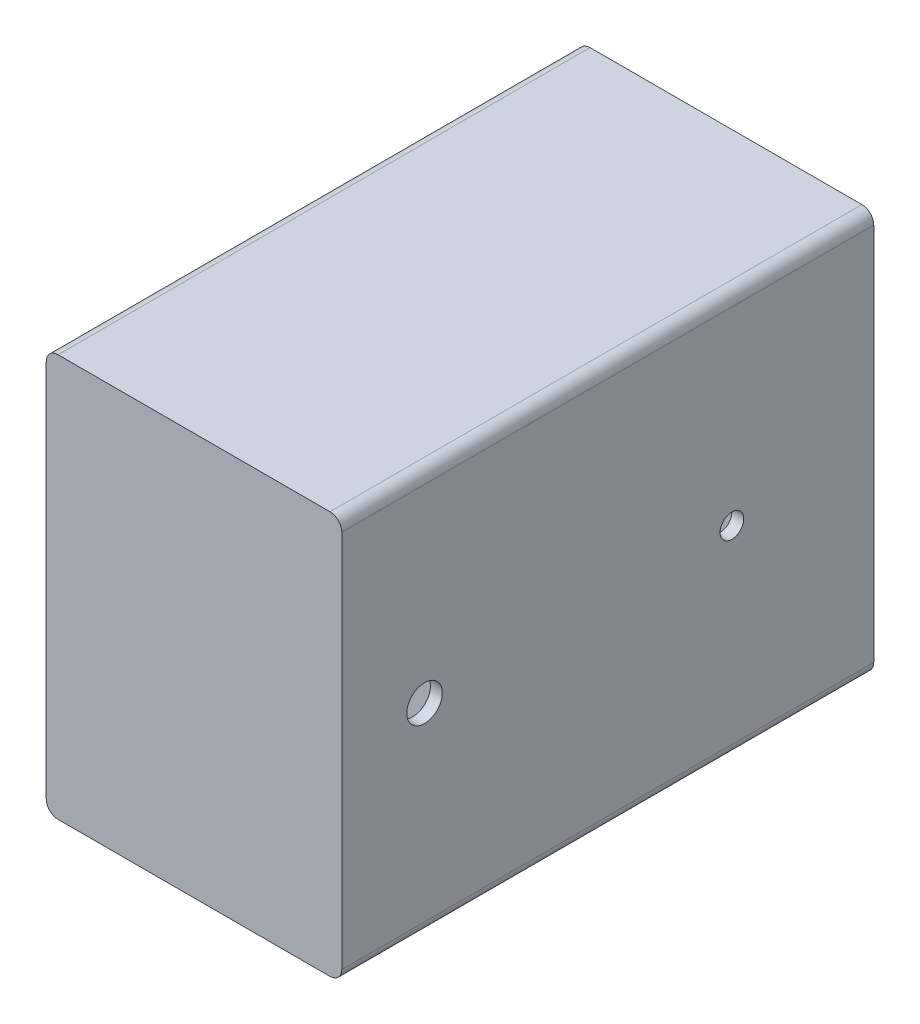
SolidWorks part; units mm, degrees
material "PE 低/中密度"
ref_plane "前视基准面" through (0, 0, 0) normal (0, 0, 1) x (1, 0, 0)
ref_plane "上视基准面" through (0, 0, 0) normal (0, 1, 0) x (1, 0, 0)
ref_plane "右视基准面" through (0, 0, 0) normal (1, 0, 0) x (0, 0, -1)
sketch "草图1" plane through (0, 0, 0) normal (0, 0, 1) x (1, 0, 0)
  line L1 (-125, 170.2) -> (125, 170.2)
  line L2 (-125, 170.2) -> (-125, -170.2)
  line L3 (-125, -170.2) -> (125, -170.2)
  line L4 (125, 170.2) -> (125, -170.2)
  line L5 (-125, 170.2) -> (125, -170.2) construction
  line L6 (-125, -170.2) -> (125, 170.2) construction
  point P0 (0, 0)
  dimension "D1" = 340.4
  dimension "D2" = 250
extrude "凸台-拉伸1" add sketch "草图1" along normal blind 450
fillet "圆角1" radius 10 4 edges at (-125, -170.2, 225) (125, -170.2, 225) (-125, 170.2, 225) (125, 170.2, 225)
sketch "草图4" plane through (125, 0, 0) normal (1, 0, 0) x (0, 0, -1)
  line L1 (-225, 160.2) -> (-225, -90.0252) construction
  line L2 (0, 160.2) -> (-450, 160.2) construction
  line L3 (-120, 0) -> (0, 0) construction
  circle A1 centre (-120, 0) radius 10
  dimension "D1" = 120
extrude "切除-拉伸1" cut sketch "草图4" against normal blind 50
sketch "草图5" plane through (0, 0, 0) normal (0, 0, -1) x (-1, 0, 0)
  line L3 (-30.5, -35.5) -> (30.5, -35.5)
  line L4 (-40.5, -25.5) -> (-40.5, 25.5)
  line L5 (-30.5, 35.5) -> (30.5, 35.5)
  line L6 (40.5, -25.5) -> (40.5, 25.5)
  line L7 (-40.5, -35.5) -> (40.5, 35.5) construction
  line L8 (-40.5, 35.5) -> (40.5, -35.5) construction
  arc A0 (-40.5, 25.5) -> (-30.5, 35.5) centre (-30.5, 25.5) cw
  arc A1 (30.5, -35.5) -> (40.5, -25.5) centre (30.5, -25.5) ccw
  arc A2 (-30.5, -35.5) -> (-40.5, -25.5) centre (-30.5, -25.5) cw
  arc A3 (30.5, 35.5) -> (40.5, 25.5) centre (30.5, 25.5) cw
  point P0 (0, 0)
  dimension "D3" = 10
  dimension "D4" = 10
  dimension "D5" = 10
  dimension "D1" = 81
  dimension "D2" = 71
extrude "切除-拉伸2" cut sketch "草图5" against normal blind 1
sketch "草图7" plane through (0, 0, 450) normal (0, 0, 1) x (1, 0, 0)
  line L1 (-120, -160.2) -> (-120, 160.2)
  line L3 (-120, 160.2) -> (115, 160.2)
  line L4 (-18.2955, -160.2) -> (-120, -160.2)
  line L5 (115, 160.2) -> (115, -160.2)
  line L7 (-18.2955, -160.2) -> (115, -160.2)
extrude "切除-拉伸3" cut sketch "草图7" against normal blind 440 from offset 5 offset against normal yes
sketch "草图8" plane through (-125, 0, 0) normal (-1, 0, 0) x (0, 0, 1)
  line L0 (380, 0) -> (450, 0) construction
  line L1 (450, 160.2) -> (450, -160.2) construction
  circle A0 centre (380, 0) radius 15
  dimension "D2" = 30
  dimension "D1" = 70
extrude "切除-拉伸4" cut sketch "草图8" against normal through all
sketch "草图11" plane through (125, 0, 0) normal (1, 0, 0) x (0, 0, -1)
  line L0 (0, 160.2) -> (-450, 160.2) construction
  line L1 (-322, 160.2) -> (-330, 160.2)
  line L3 (-330, 160.2) -> (-330, -160.2)
  line L4 (-450, -160.2) -> (0, -160.2) construction
  line L5 (-330, -160.2) -> (-322, -160.2)
  line L6 (-322, -160.2) -> (-322, 160.2)
  dimension "D3" = 8
extrude "凸台-拉伸2" add sketch "草图11" against normal blind 235 from offset 5
